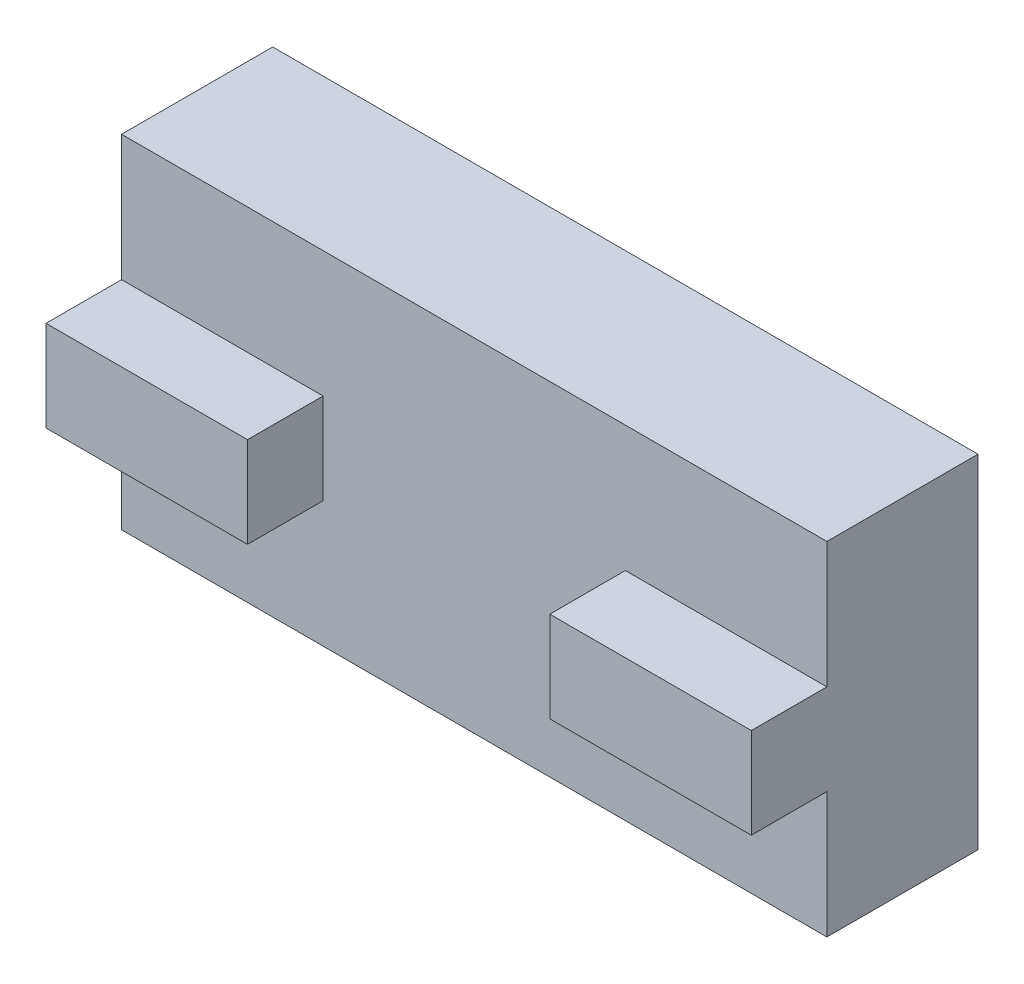
SolidWorks part; units mm, degrees
ref_plane "Plane1" through (0, 0, 0) normal (0, 0, 1) x (1, 0, 0)
ref_plane "Plane2" through (0, 0, 0) normal (0, 1, 0) x (1, 0, 0)
ref_plane "Plane3" through (0, 0, 0) normal (1, 0, 0) x (0, 0, -1)
sketch "Sketch1" plane through (0, 0, 0) normal (0, 0, 1) x (1, 0, 0)
  line L0 (-500, 240) -> (200, 240)
  line L1 (-500, 240) -> (-500, -100)
  line L2 (200, -100) -> (-500, -100)
  line L3 (200, -100) -> (200, 240)
  dimension "D1" = 340
  dimension "D2" = 700
  dimension "D3" = 500
  dimension "D4" = 100
extrude "Base-Extrude" add sketch "Sketch1" along normal blind 150
sketch "Sketch2" plane through (0, 0, 150) normal (0, 0, 1) x (1, 0, 0)
  line L0 (-500, 115) -> (200, 115)
  line L1 (-500, 115) -> (-500, 25)
  line L2 (200, 25) -> (-500, 25)
  line L3 (200, 25) -> (200, 115)
  line L4 (-500, 240) -> (-500, -100) construction
  line L5 (200, -100) -> (200, 240) construction
  line L6 (-500, 240) -> (200, 240) construction
  dimension "D1" = 90
  dimension "D2" = 125
extrude "Boss-Extrude1" add sketch "Sketch2" along normal blind 75
sketch "Sketch3" plane through (0, 0, 225) normal (0, 0, 1) x (1, 0, 0)
  line L0 (0, 20) -> (-300, 20)
  line L1 (0, 20) -> (0, 120)
  line L2 (-300, 120) -> (0, 120)
  line L3 (-300, 120) -> (-300, 20)
extrude "Cut-Extrude1" cut sketch "Sketch3" against normal up to surface (75 mm away)
